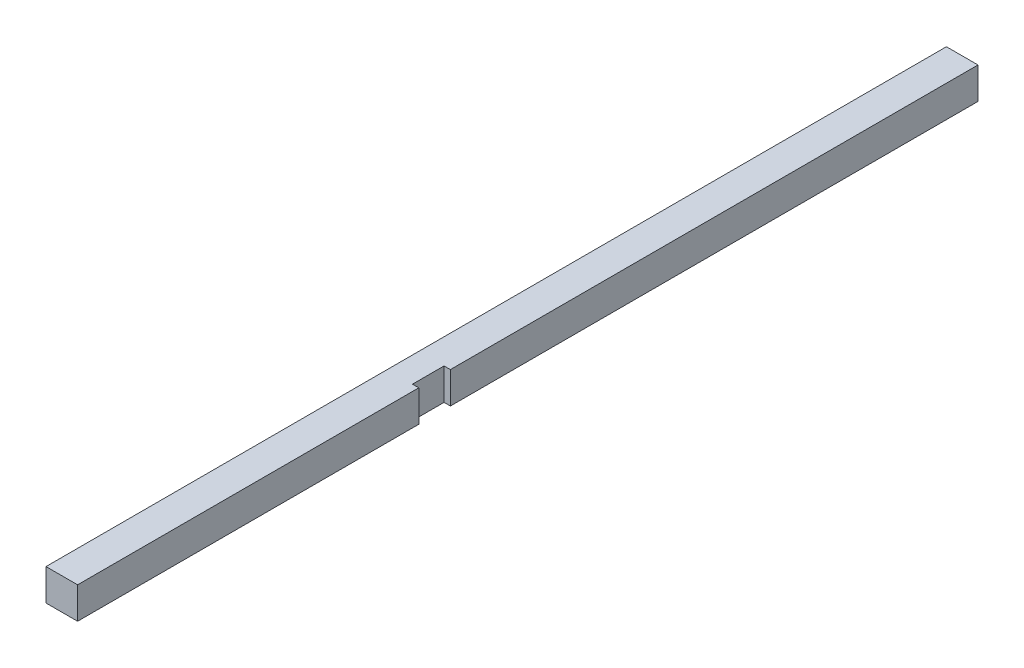
SolidWorks part; units mm, degrees
ref_plane "Plan de face" through (0, 0, 0) normal (0, 0, 1) x (1, 0, 0)
ref_plane "Plan de dessus" through (0, 0, 0) normal (0, 1, 0) x (1, 0, 0)
ref_plane "Plan de droite" through (0, 0, 0) normal (1, 0, 0) x (0, 0, -1)
sketch "Esquisse1" plane through (0, 0, 0) normal (0, 0, 1) x (1, 0, 0)
  line L1 (0, 0) -> (10, 0)
  line L2 (0, 0) -> (0, 10)
  line L3 (0, 10) -> (10, 10)
  line L4 (10, 0) -> (10, 10)
  dimension "D1" = 10
  dimension "D2" = 10
extrude "Boss.-Extru.1" add sketch "Esquisse1" along normal blind 285
sketch "Esquisse2" plane through (0, 10, 0) normal (0, 1, 0) x (1, 0, 0)
  line L0 (10, -285) -> (10, 0) construction
  line L1 (10, -177) -> (8, -177)
  line L2 (10, -177) -> (10, -167)
  line L3 (10, -167) -> (8, -167)
  line L4 (8, -177) -> (8, -167)
  line L5 (10, -285) -> (0, -285) construction
  dimension "D1" = 2
  dimension "D2" = 10
  dimension "D3" = 108
extrude "Enlèv. mat.-Extru.1" cut sketch "Esquisse2" against normal through all
